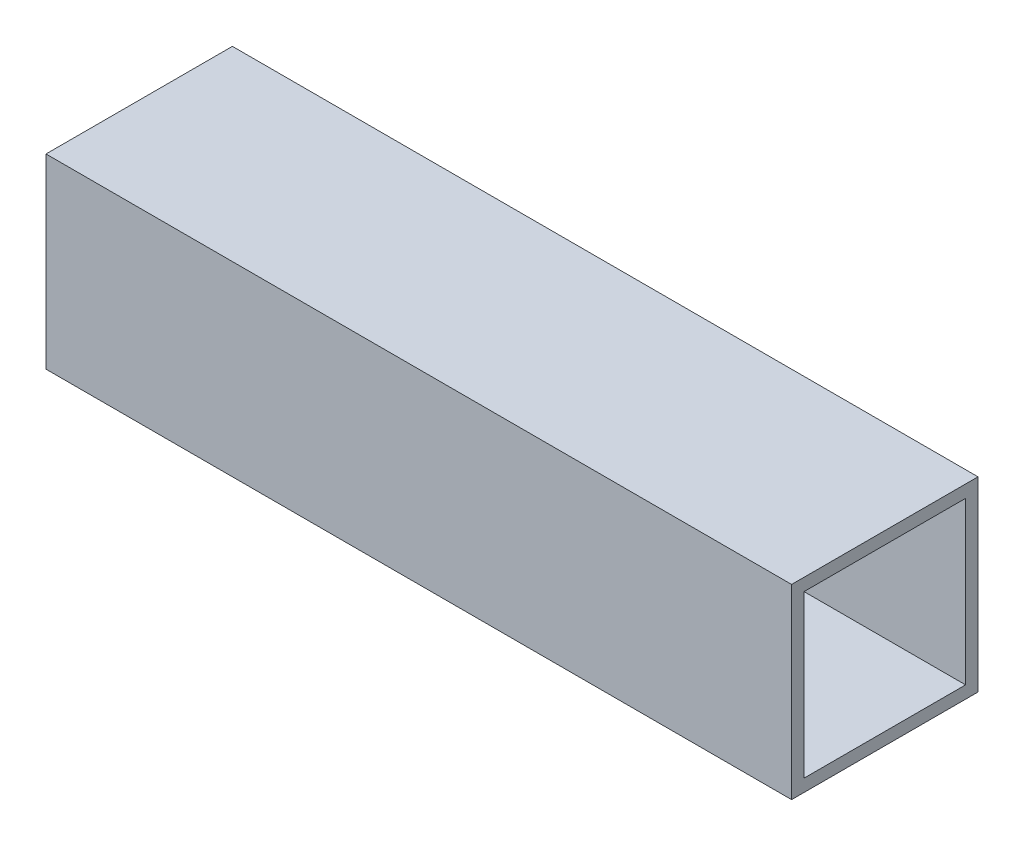
SolidWorks part; units mm, degrees
ref_plane "Front" through (0, 0, 0) normal (0, 0, 1) x (1, 0, 0)
ref_plane "Top" through (0, 0, 0) normal (0, 1, 0) x (1, 0, 0)
ref_plane "Right" through (0, 0, 0) normal (1, 0, 0) x (0, 0, -1)
sketch "草图1" plane through (0, 0, 0) normal (0, 0, 1) x (1, 0, 0)
  line L0 (0, 0) -> (-60, 0)
  dimension "D1" = 60
other "铝管 15X15X1(1)"
ref_plane "基准面1" through (0, 0, 0) normal (-1, 0, 0) x (0, -1, 0)
sketch "草图11" plane through (0, 0, 0) normal (-1, 0, 0) x (0, -1, 0)
  line L1 (-7.5, -7.5) -> (7.5, -7.5)
  line L2 (-7.5, -7.5) -> (-7.5, 7.5)
  line L3 (-7.5, 7.5) -> (7.5, 7.5)
  line L4 (7.5, -7.5) -> (7.5, 7.5)
  line L5 (-7.5, -7.5) -> (7.5, 7.5) construction
  line L6 (-7.5, 7.5) -> (7.5, -7.5) construction
  line L7 (-6.5, -6.5) -> (6.5, -6.5)
  line L8 (-6.5, -6.5) -> (-6.5, 6.5)
  line L9 (-6.5, 6.5) -> (6.5, 6.5)
  line L10 (6.5, -6.5) -> (6.5, 6.5)
  line L11 (-6.5, -6.5) -> (6.5, 6.5) construction
  line L12 (-6.5, 6.5) -> (6.5, -6.5) construction
  point P0 (0, 0)
  point P6 (0, 0)
  point P11 (0, 0)
  dimension "D1" = 15
  dimension "D2" = 15
  dimension "D3" = 13
  dimension "D4" = 13
